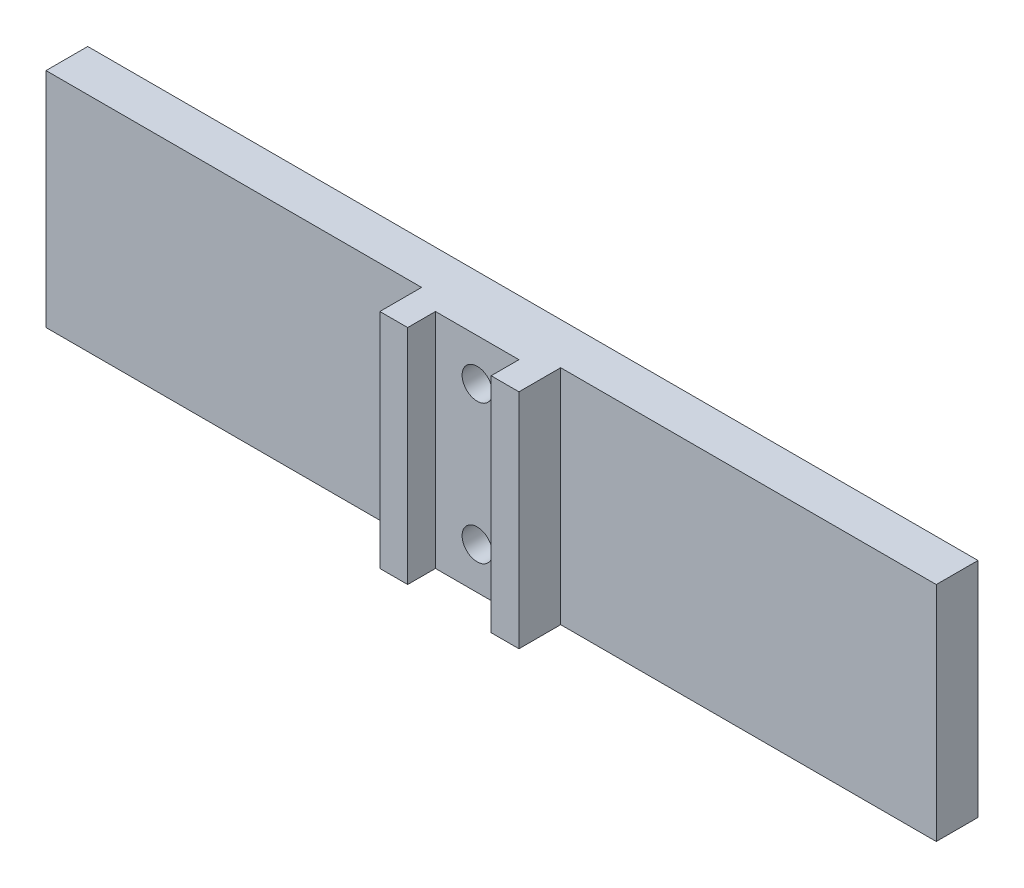
SolidWorks part; units mm, degrees
ref_plane "Front Plane" through (0, 0, 0) normal (0, 0, 1) x (1, 0, 0)
ref_plane "Top Plane" through (0, 0, 0) normal (0, 1, 0) x (1, 0, 0)
ref_plane "Right Plane" through (0, 0, 0) normal (1, 0, 0) x (0, 0, -1)
sketch "Sketch1" plane through (0, 0, 0) normal (0, 0, 1) x (1, 0, 0)
  line L1 (0, 0) -> (101.6, 0)
  line L2 (0, 0) -> (0, 25.4)
  line L3 (0, 25.4) -> (101.6, 25.4)
  line L4 (101.6, 0) -> (101.6, 25.4)
  dimension "D1" = 25.4
  dimension "D2" = 101.6
extrude "Boss-Extrude1" add sketch "Sketch1" along normal blind 9.525
sketch "Sketch2" plane through (0, 25.4, 0) normal (0, 1, 0) x (1, 0, 0)
  line L0 (50.8, 0) -> (50.8, -9.525) construction
  line L1 (101.6, 0) -> (0, 0) construction
  line L2 (101.6, -9.525) -> (0, -9.525) construction
  line L3 (55.5625, -9.525) -> (55.5625, -6.35)
  line L4 (0, -9.525) -> (42.8625, -9.525)
  line L5 (0, -9.525) -> (0, -4.7625)
  line L6 (0, -4.7625) -> (42.8625, -4.7625)
  line L7 (42.8625, -9.525) -> (42.8625, -4.7625)
  line L8 (55.5625, -9.525) -> (46.0375, -9.525)
  line L10 (55.5625, -6.35) -> (46.0375, -6.35)
  line L11 (46.0375, -9.525) -> (46.0375, -6.35)
  line L12 (58.7375, -9.525) -> (58.7375, -4.7625)
  line L13 (101.6, -4.7625) -> (58.7375, -4.7625)
  line L14 (101.6, -9.525) -> (101.6, -4.7625)
  line L15 (101.6, -9.525) -> (58.7375, -9.525)
  dimension "D1" = 4.7625
  dimension "D2" = 6.35
  dimension "D3" = 9.525
  dimension "D4" = 3.175
extrude "Cut-Extrude1" cut sketch "Sketch2" against normal through all
hole_wizard "#8-32 Tapped Hole1" positions "Sketch7" profile "Sketch8" tap size "#8-32" standard "ANSI Inch" end condition through all
sketch "Sketch7" plane through (0, 0, 6.35) normal (0, 0, 1) x (1, 0, 0)
  line L0 (55.5625, 12.7) -> (46.0375, 12.7) construction
  line L1 (55.5625, 0) -> (55.5625, 25.4) construction
  line L2 (46.0375, 0) -> (46.0375, 25.4) construction
  line L4 (50.8, 25.4) -> (50.8, 0) construction
  line L5 (55.5625, 25.4) -> (46.0375, 25.4) construction
  line L6 (55.5625, 0) -> (46.0375, 0) construction
  point P16 (50.8, 4.7625)
  point P19 (50.8, 20.6375)
  dimension "D1" = 7.9375
sketch "Sketch8" plane through (50.8, 4.7625, 6.35) normal (1, 0, 0) x (0, -1, 0)
  line L0 (0, 0) -> (0, 6.35)
  line L1 (0, 6.35) -> (1.7272, 6.35)
  line L2 (1.7272, 6.35) -> (1.7272, 0)
  line L5 (1.7272, 0) -> (0, 0)
  line L11 (0, -6.35) -> (0, 107.95) construction
  dimension "Thread Major Dia." = 3.4544
  dimension "Thru Tap Drill Depth" = 6.35
